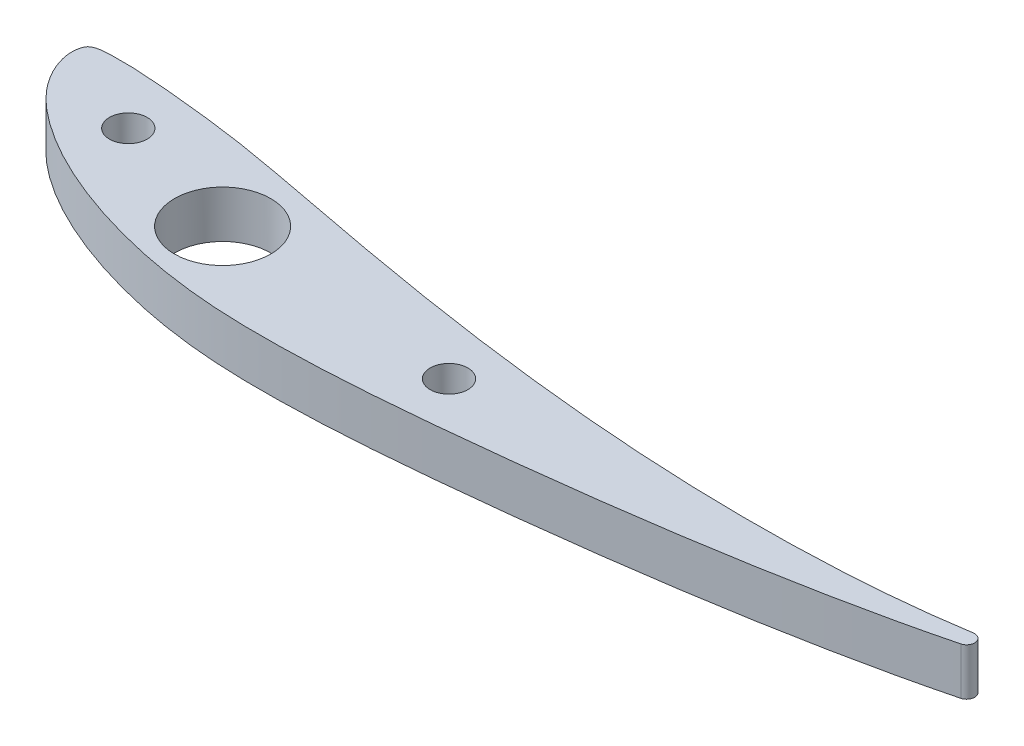
SolidWorks part; units mm, degrees
material "6061-T6 (SS)"
ref_plane "Front Plane" through (0, 0, 0) normal (0, 0, 1) x (1, 0, 0)
ref_plane "Top Plane" through (0, 0, 0) normal (0, 1, 0) x (1, 0, 0)
ref_plane "Right Plane" through (0, 0, 0) normal (1, 0, 0) x (0, 0, -1)
curve "Curve1"
  spline degree 3 poles (-3.7953, 0, -0.0099) (-3.8135, 0, 0.0025) (-3.7975, 0, -0.0094) (-3.7869, 0, -0.0198) (-3.7634, 0, -0.0415) (-3.7356, 0, -0.0646) (-3.6977, 0, -0.0879) (-3.6505, 0, -0.1105) (-3.5935, 0, -0.134) (-3.5268, 0, -0.1582) (-3.4508, 0, -0.1829) (-3.3657, 0, -0.2079) (-3.2722, 0, -0.233) (-3.1706, 0, -0.258) (-3.0616, 0, -0.2828) (-2.9459, 0, -0.3071) (-2.8241, 0, -0.331) (-2.697, 0, -0.354) (-2.5653, 0, -0.3761) (-2.4298, 0, -0.3971) (-2.2915, 0, -0.417) (-2.1511, 0, -0.4356) (-2.0096, 0, -0.4529) (-1.8684, 0, -0.4689) (-1.7284, 0, -0.4834) (-1.5908, 0, -0.496) (-1.4567, 0, -0.506) (-1.3267, 0, -0.5129) (-1.2016, 0, -0.5159) (-1.082, 0, -0.5155) (-0.9682, 0, -0.5097) (-0.8601, 0, -0.4978) (-0.7573, 0, -0.4811) (-0.6597, 0, -0.4593) (-0.5675, 0, -0.4338) (-0.481, 0, -0.4051) (-0.4006, 0, -0.3736) (-0.3268, 0, -0.3398) (-0.2599, 0, -0.3041) (-0.2001, 0, -0.2671) (-0.148, 0, -0.2293) (-0.1034, 0, -0.1913) (-0.0671, 0, -0.1529) (-0.0392, 0, -0.1144) (-0.0186, 0, -0.0769) (-0.0054, 0, -0.0412) (0.0009, 0, -0.0084) (-0.0003, 0, 0.0194) (-0.0075, 0, 0.0449) (-0.0341, 0, 0.0576) (-0.0699, 0, 0.0593) (-0.1188, 0, 0.0611) (-0.1803, 0, 0.0584) (-0.2538, 0, 0.0535) (-0.3383, 0, 0.0457) (-0.433, 0, 0.0352) (-0.5376, 0, 0.0216) (-0.6518, 0, 0.0027) (-0.7763, 0, -0.0211) (-0.9117, 0, -0.0469) (-1.0573, 0, -0.0742) (-1.2123, 0, -0.1018) (-1.3754, 0, -0.1287) (-1.5454, 0, -0.154) (-1.7209, 0, -0.1767) (-1.9002, 0, -0.1962) (-2.0817, 0, -0.2116) (-2.2636, 0, -0.2225) (-2.4439, 0, -0.2285) (-2.6207, 0, -0.2293) (-2.792, 0, -0.2247) (-2.9559, 0, -0.215) (-3.1104, 0, -0.2002) (-3.2537, 0, -0.1809) (-3.3838, 0, -0.1577) (-3.4993, 0, -0.1313) (-3.598, 0, -0.103) (-3.6788, 0, -0.0729) (-3.7364, 0, -0.0453) (-3.7789, 0, -0.0198) (-3.7953, 0, -0.0099) (-3.8135, 0, 0.0025) (-3.7975, 0, -0.0094) knots -0.009748 -0.004147 -0.001 0 0.00098 0.003649 0.007483 0.012095 0.017526 0.024052 0.031783 0.040678 0.05071 0.061833 0.073989 0.087118 0.101145 0.115991 0.13157 0.147788 0.164551 0.181758 0.199312 0.217095 0.23499 0.252857 0.270541 0.287887 0.304773 0.321101 0.336806 0.3518 0.366031 0.379616 0.392653 0.40517 0.417172 0.428604 0.439419 0.449597 0.459102 0.467908 0.475988 0.483309 0.489875 0.495803 0.501149 0.505903 0.510047 0.513579 0.516447 0.51935 0.523823 0.529974 0.537716 0.546968 0.557637 0.56962 0.582804 0.597247 0.613135 0.630444 0.649056 0.668822 0.689595 0.71119 0.733427 0.756094 0.778989 0.80189 0.824567 0.846792 0.868338 0.888978 0.908492 0.926659 0.943286 0.958169 0.971136 0.981956 0.990252 0.995853 0.999 1 1.00098 1.003649 1.007483 periodic
sketch "Sketch1" plane through (0, 0, 0) normal (0, 1, 0) x (1, 0, 0)
  line L0 (150, 0) -> (0, 0) construction
  line L1 (0, -0.0038) -> (0, 31241.5392) construction
  spline S1 degree 3 poles (149.5079, -0.3714) (150.1359, 0.0969) (149.4197, -0.3897) (148.7771, -0.7786) (147.1043, -1.7836) (144.8353, -2.8707) (141.6549, -4.0588) (137.7688, -5.1723) (133.2225, -6.2132) (128.0998, -7.1299) (122.4608, -7.8917) (116.3789, -8.4765) (109.9265, -8.8619) (103.1812, -9.043) (96.2202, -9.0156) (89.1212, -8.7815) (81.9612, -8.3539) (74.815, -7.7495) (67.7544, -6.9843) (60.846, -6.0927) (54.1519, -5.1006) (47.7299, -4.0446) (41.6298, -2.9598) (35.8964, -1.8873) (30.5658, -0.8714) (25.6639, 0.0621) (21.1664, 0.8062) (17.0513, 1.3384) (13.3206, 1.7532) (9.9925, 2.0595) (7.1011, 2.2505) (4.6785, 2.3541) (2.7521, 2.2857) (1.344, 2.2153) (0.2968, 1.7167) (0.0154, 0.7128) (-0.032, -0.3816) (0.2161, -1.6755) (0.7365, -3.0773) (1.5481, -4.5536) (2.6468, -6.0709) (4.0769, -7.5826) (5.8318, -9.0754) (7.8858, -10.5656) (10.2383, -12.0217) (12.8744, -13.424) (15.7798, -14.7564) (18.9451, -15.9919) (22.3507, -17.1239) (25.9822, -18.1259) (29.824, -18.9801) (33.8724, -19.6391) (38.1281, -20.1047) (42.6087, -20.3336) (47.3157, -20.3444) (52.2405, -20.2257) (57.3578, -19.953) (62.6391, -19.5573) (68.0544, -19.0596) (73.5654, -18.4879) (79.1274, -17.8529) (84.6942, -17.1705) (90.2214, -16.436) (95.6689, -15.6517) (101.0019, -14.8238) (106.1858, -13.9507) (111.1907, -13.0437) (115.9852, -12.104) (120.5412, -11.1432) (124.8309, -10.1662) (128.8288, -9.1792) (132.5118, -8.1893) (135.8597, -7.2055) (138.8538, -6.2326) (141.4784, -5.2789) (143.7214, -4.3511) (145.5793, -3.4622) (147.0733, -2.5452) (148.1654, -1.6356) (149.091, -0.7807) (149.5079, -0.3714) (150.1359, 0.0969) (149.4197, -0.3897) knots -0.007483 -0.003649 -0.00098 0 0.001 0.004147 0.009748 0.018044 0.028864 0.041831 0.056714 0.073341 0.091508 0.111022 0.131662 0.153208 0.175433 0.19811 0.221011 0.243906 0.266573 0.28881 0.310405 0.331178 0.350944 0.369556 0.386865 0.402753 0.417196 0.43038 0.442363 0.453032 0.462284 0.470026 0.476177 0.48065 0.483553 0.486421 0.489953 0.494097 0.498851 0.504197 0.510125 0.516691 0.524012 0.532092 0.540898 0.550403 0.560581 0.571396 0.582828 0.59483 0.607347 0.620384 0.633969 0.6482 0.663194 0.678899 0.695227 0.712113 0.729459 0.747143 0.76501 0.782905 0.800688 0.818242 0.835449 0.852212 0.86843 0.884009 0.898855 0.912882 0.926011 0.938167 0.94929 0.959322 0.968217 0.975948 0.982474 0.987905 0.992517 0.996351 0.99902 1 1.001 1.004147 1.009748 only from (150, 0) to (150, 0)
  dimension "D1" = 150
extrude "Boss-Extrude1" add sketch "Sketch1" along normal blind 6.35
sketch "Sketch3" plane through (0, 6.35, 0) normal (0, 1, 0) x (1, 0, 0)
  line L0 (-1000, 0) -> (49000, 0) construction
  line L1 (30.48, -10.16) -> (30.48, 0) construction
  circle A0 centre (30.48, -10.16) radius 6.477
  dimension "D1" = 12.954
  dimension "D3" = 30.48
  dimension "D4" = 10.16
extrude "Cut-Extrude2" cut sketch "Sketch3" against normal through all both and the other way through all
sketch "Sketch4" plane through (0, 6.35, 0) normal (0, 1, 0) x (1, 0, 0)
  line L0 (-1000, 0) -> (49000, 0) construction
  line L1 (12.7, -5.08) -> (12.7, 0) construction
  line L2 (63.5, -12.7) -> (63.5, 0) construction
  circle A0 centre (12.7, -5.08) radius 2.54
  circle A1 centre (63.5, -12.7) radius 2.54
  dimension "D1" = 5.08
  dimension "D3" = 12.7
  dimension "D4" = 5.08
  dimension "D6" = 12.7
  dimension "D7" = 63.5
extrude "Cut-Extrude3" cut sketch "Sketch4" against normal through all both and the other way through all
sketch "Sketch5" plane through (0, 6.35, 0) normal (0, 1, 0) x (1, 0, 0)
  line L0 (128.8457, -9.1608) -> (154.9303, -7.4494)
  line L1 (154.9303, -7.4494) -> (149.5544, 4.7563)
  line L2 (149.5544, 4.7563) -> (128.3461, -7.0516)
  arc A0 (128.3461, -7.0516) -> (128.8457, -9.1608) centre (128.5959, -8.1062) cw
  spline S0 degree 3 poles (149.5079, -0.3714) (150.1359, 0.0969) (149.4197, -0.3897) (148.7771, -0.7786) (147.1043, -1.7836) (144.8353, -2.8707) (141.6549, -4.0588) (137.7688, -5.1723) (133.2225, -6.2132) (128.0998, -7.1299) (122.4608, -7.8917) (116.3789, -8.4765) (109.9265, -8.8619) (103.1812, -9.043) (96.2202, -9.0156) (89.1212, -8.7815) (81.9612, -8.3539) (74.815, -7.7495) (67.7544, -6.9843) (60.846, -6.0927) (54.1519, -5.1006) (47.7299, -4.0446) (41.6298, -2.9598) (35.8964, -1.8873) (30.5658, -0.8714) (25.6639, 0.0621) (21.1664, 0.8062) (17.0513, 1.3384) (13.3206, 1.7532) (9.9925, 2.0595) (7.1011, 2.2505) (4.6785, 2.3541) (2.7521, 2.2857) (1.344, 2.2153) (0.2968, 1.7167) (0.0154, 0.7128) (-0.032, -0.3816) (0.2161, -1.6755) (0.7365, -3.0773) (1.5481, -4.5536) (2.6468, -6.0709) (4.0769, -7.5826) (5.8318, -9.0754) (7.8858, -10.5656) (10.2383, -12.0217) (12.8744, -13.424) (15.7798, -14.7564) (18.9451, -15.9919) (22.3507, -17.1239) (25.9822, -18.1259) (29.824, -18.9801) (33.8724, -19.6391) (38.1281, -20.1047) (42.6087, -20.3336) (47.3157, -20.3444) (52.2405, -20.2257) (57.3578, -19.953) (62.6391, -19.5573) (68.0544, -19.0596) (73.5654, -18.4879) (79.1274, -17.8529) (84.6942, -17.1705) (90.2214, -16.436) (95.6689, -15.6517) (101.0019, -14.8238) (106.1858, -13.9507) (111.1907, -13.0437) (115.9852, -12.104) (120.5412, -11.1432) (124.8309, -10.1662) (128.8288, -9.1792) (132.5118, -8.1893) (135.8597, -7.2055) (138.8538, -6.2326) (141.4784, -5.2789) (143.7214, -4.3511) (145.5793, -3.4622) (147.0733, -2.5452) (148.1654, -1.6356) (149.091, -0.7807) (149.5079, -0.3714) (150.1359, 0.0969) (149.4197, -0.3897) knots -0.007483 -0.003649 -0.00098 0 0.001 0.004147 0.009748 0.018044 0.028864 0.041831 0.056714 0.073341 0.091508 0.111022 0.131662 0.153208 0.175433 0.19811 0.221011 0.243906 0.266573 0.28881 0.310405 0.331178 0.350944 0.369556 0.386865 0.402753 0.417196 0.43038 0.442363 0.453032 0.462284 0.470026 0.476177 0.48065 0.483553 0.486421 0.489953 0.494097 0.498851 0.504197 0.510125 0.516691 0.524012 0.532092 0.540898 0.550403 0.560581 0.571396 0.582828 0.59483 0.607347 0.620384 0.633969 0.6482 0.663194 0.678899 0.695227 0.712113 0.729459 0.747143 0.76501 0.782905 0.800688 0.818242 0.835449 0.852212 0.86843 0.884009 0.898855 0.912882 0.926011 0.938167 0.94929 0.959322 0.968217 0.975948 0.982474 0.987905 0.992517 0.996351 0.99902 1 1.001 1.004147 1.009748 only from (150, 0) to (150, 0) construction
extrude "Cut-Extrude4" cut sketch "Sketch5" against normal through all both and the other way through all
